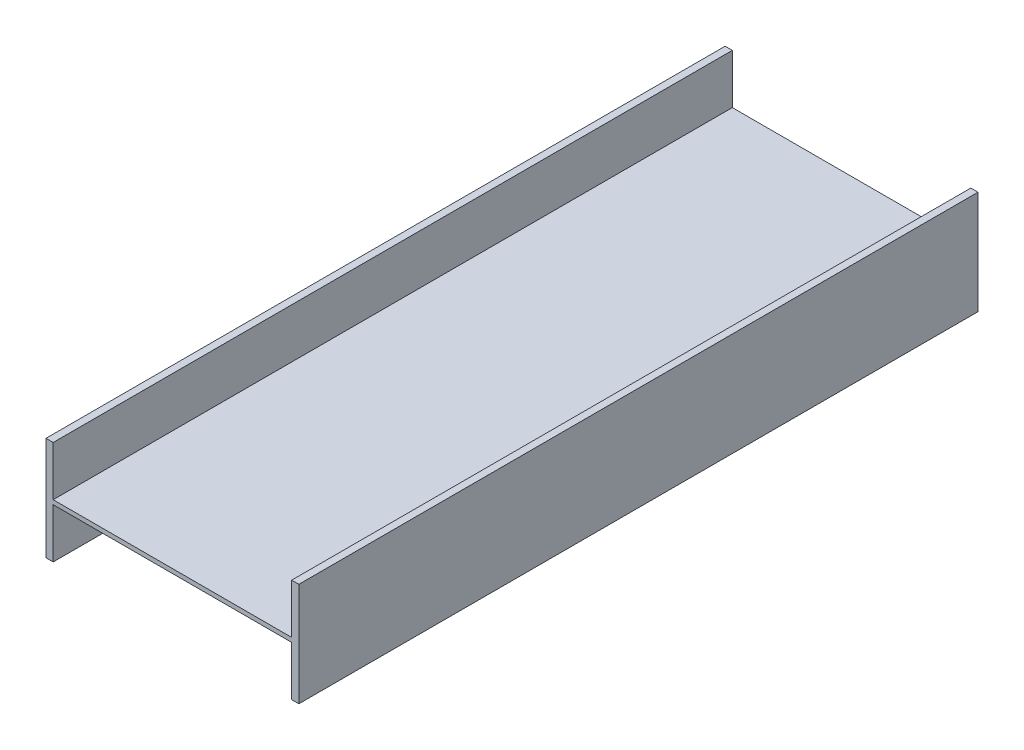
SolidWorks part; units mm, degrees
ref_plane "Front Plane" through (0, 0, 0) normal (0, 0, 1) x (1, 0, 0)
ref_plane "Top Plane" through (0, 0, 0) normal (0, 1, 0) x (1, 0, 0)
ref_plane "Right Plane" through (0, 0, 0) normal (1, 0, 0) x (0, 0, -1)
sketch "Sketch1" plane through (0, 0, 0) normal (0, 0, 1) x (1, 0, 0)
  line L1 (-526.75, -9.525) -> (526.75, -9.525)
  line L2 (-526.75, -9.525) -> (-526.75, 9.525)
  line L3 (-526.75, 9.525) -> (526.75, 9.525)
  line L4 (526.75, -9.525) -> (526.75, 9.525)
  line L5 (-526.75, -9.525) -> (526.75, 9.525) construction
  line L6 (-526.75, 9.525) -> (526.75, -9.525) construction
  line L7 (526.75, 228.6) -> (558.5, 228.6)
  line L8 (526.75, 228.6) -> (526.75, -228.6)
  line L9 (526.75, -228.6) -> (558.5, -228.6)
  line L10 (558.5, 228.6) -> (558.5, -228.6)
  line L11 (526.75, 228.6) -> (558.5, -228.6) construction
  line L12 (526.75, -228.6) -> (558.5, 228.6) construction
  line L13 (-558.5, -228.6) -> (-526.75, -228.6)
  line L14 (-558.5, -228.6) -> (-558.5, 228.6)
  line L15 (-558.5, 228.6) -> (-526.75, 228.6)
  line L16 (-526.75, -228.6) -> (-526.75, 228.6)
  line L17 (-558.5, -228.6) -> (-526.75, 228.6) construction
  line L18 (-558.5, 228.6) -> (-526.75, -228.6) construction
  point P0 (0, 0)
  point P5 (542.625, 0)
  point P12 (-542.625, 0)
  dimension "D1" = 19.05
  dimension "D2" = 1117
  dimension "D3" = 31.75
  dimension "D4" = 457.2
extrude "Boss-Extrude1" add sketch "Sketch1" along normal blind 3000 contours L13 L16 L2 L15 L14 | L1 L4 L3 L2 | L10 L7 L8 L4 L9
